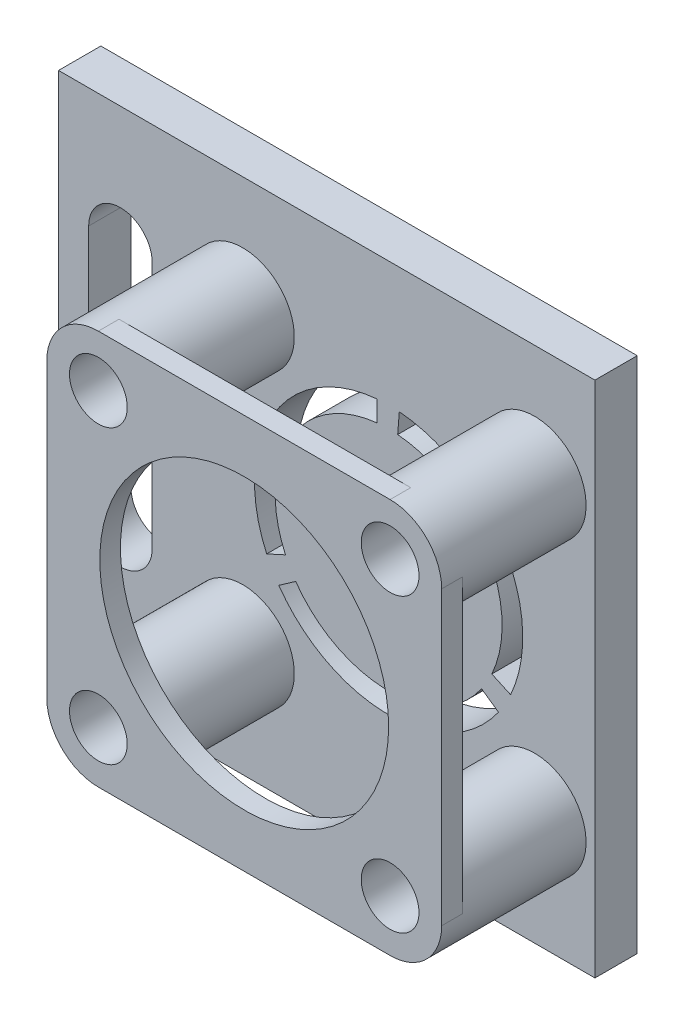
SolidWorks part; units mm, degrees
ref_plane "Front Plane" through (0, 0, 0) normal (0, 0, 1) x (1, 0, 0)
ref_plane "Top Plane" through (0, 0, 0) normal (0, 1, 0) x (1, 0, 0)
ref_plane "Right Plane" through (0, 0, 0) normal (1, 0, 0) x (0, 0, -1)
sketch "Sketch1" plane through (0, 0, 0) normal (0, 0, 1) x (1, 0, 0)
  line L1 (-13, -12.55) -> (13, -12.55)
  line L2 (-13, -12.55) -> (-13, 12.55)
  line L3 (-13, 12.55) -> (13, 12.55)
  line L4 (13, -12.55) -> (13, 12.55)
  line L5 (-13, -12.55) -> (13, 12.55) construction
  line L6 (-13, 12.55) -> (13, -12.55) construction
  point P0 (0, 0)
  dimension "D1" = 26
  dimension "D2" = 25.1
extrude "Boss-Extrude1" add sketch "Sketch1" along normal blind 2.05
sketch "Sketch2" plane through (0, 0, 2.05) normal (0, 0, 1) x (1, 0, 0)
  line L0 (-10, 6.75) -> (-10, -5.25) construction
  line L1 (-8.46, 6.75) -> (-8.46, -5.25)
  line L2 (-11.54, 6.75) -> (-11.54, -5.25)
  line L3 (13, 12.55) -> (-13, 12.55) construction
  line L4 (2.438, 5.4712) -> (2.438, 6.4757)
  line L5 (3.5177, 6.4794) -> (3.438, 5.4825)
  line L6 (8.9115, -2.7025) -> (8.0021, -2.2868)
  line L7 (7.5053, -3.1547) -> (8.3245, -3.7282)
  line L8 (-2.3245, -3.7282) -> (-1.5053, -3.1547)
  line L9 (-2.9115, -2.7025) -> (-2.0021, -2.2868)
  line L10 (13, -12.55) -> (13, 12.55) construction
  arc A0 (-8.46, 6.75) -> (-11.54, 6.75) centre (-10, 6.75) ccw
  arc A1 (-11.54, -5.25) -> (-8.46, -5.25) centre (-10, -5.25) ccw
  circle A3 centre (3, 0) radius 6.5
  circle A4 centre (3, 0) radius 5.5
  point P2 (-10, 0.75)
  dimension "D2" = 1.54
  dimension "D4" = 10
  dimension "D5" = 13
  dimension "D6" = 5.8
  dimension "D1" = 12
  dimension "D3" = 13
  dimension "D9" = 1
  dimension "D10" = 110
  dimension "D11" = 110
  dimension "D12" = 1
  dimension "D8" = 1
extrude "Cut-Extrude1" cut sketch "Sketch2" against normal through all
sketch "Sketch3" plane through (0, 0, 2.05) normal (0, 0, 1) x (1, 0, 0)
  line L0 (-4.0711, -7.0711) -> (10.0711, 7.0711) construction
  line L1 (-4.0711, 7.0711) -> (10.0711, -7.0711) construction
  circle A0 centre (-4.0711, 7.0711) radius 2.5
  circle A1 centre (10.0711, 7.0711) radius 2.5
  circle A2 centre (10.0711, -7.0711) radius 2.5
  circle A3 centre (-4.0711, -7.0711) radius 2.5
  arc A4 (-1.5053, -3.1547) -> (7.5053, -3.1547) centre (3, 0) ccw construction
  arc A5 (-1.5053, -3.1547) -> (7.5053, -3.1547) centre (3, 0) ccw
  dimension "D2" = 5
  dimension "D6" = 10
  dimension "D5" = 90
extrude "Boss-Extrude2" add sketch "Sketch3" along normal blind 6 contours A0 | A1 | A2 | A3
sketch "Sketch4" plane through (0, 0, 8.05) normal (0, 0, 1) x (1, 0, 0)
  line L4 (-4.0711, 9.5711) -> (10.0711, 9.5711)
  line L5 (12.5711, 7.0711) -> (12.5711, -7.0711)
  line L6 (-6.5711, -7.0711) -> (-6.5711, 7.0711)
  line L8 (10.0711, -9.5711) -> (-4.0711, -9.5711)
  circle A2 centre (-4.0711, -7.0711) radius 2.5 construction
  circle A3 centre (10.0711, -7.0711) radius 2.5 construction
  circle A4 centre (10.0711, 7.0711) radius 2.5 construction
  circle A5 centre (-4.0711, 7.0711) radius 2.5 construction
  arc A6 (-6.5711, -7.0711) -> (-4.0711, -9.5711) centre (-4.0711, -7.0711) ccw
  arc A7 (10.0711, -9.5711) -> (12.5711, -7.0711) centre (10.0711, -7.0711) ccw
  arc A8 (12.5711, 7.0711) -> (10.0711, 9.5711) centre (10.0711, 7.0711) ccw
  arc A9 (-4.0711, 9.5711) -> (-6.5711, 7.0711) centre (-4.0711, 7.0711) ccw
  circle A10 centre (3, 0) radius 7
  point P13 (3, 9.5711)
  point P22 (-6.5711, 0)
  dimension "D1" = 14
extrude "Boss-Extrude3" add sketch "Sketch4" along normal blind 1
sketch "Sketch5" plane through (0, 0, 9.05) normal (0, 0, 1) x (1, 0, 0)
  circle A0 centre (10.0711, 7.0711) radius 2.5 construction
  circle A1 centre (10.0711, -7.0711) radius 2.5 construction
  circle A2 centre (-4.0711, 7.0711) radius 2.5 construction
  circle A3 centre (-4.0711, -7.0711) radius 2.5 construction
  circle A4 centre (10.0711, 7.0711) radius 2.5
  circle A5 centre (10.0711, -7.0711) radius 2.5
  circle A6 centre (-4.0711, 7.0711) radius 2.5
  circle A7 centre (-4.0711, -7.0711) radius 2.5
  circle A8 centre (-4.0711, -7.0711) radius 1.4
  circle A9 centre (-4.0711, 7.0711) radius 1.4
  circle A10 centre (10.0711, 7.0711) radius 1.4
  circle A11 centre (10.0711, -7.0711) radius 1.4
  dimension "D1" = 2.8
extrude "Cut-Extrude2" cut sketch "Sketch5" against normal up to surface (9.05 mm away) contours A8 | A9 | A10 | A11 up to face at (-10, 0.75, 0)
ref_plane "Plane1" [suppressed] through (0, 0, 5) normal (0, 0, 1) x (1, 0, 0)
sketch "Sketch7" [suppressed] plane through (0, 0, 5) normal (0, 0, 1) x (1, 0, 0)
  line L0 (19.205, -8.5711) -> (18.7482, -8.5711)
  line L1 (20.9371, -8.5711) -> (21.8031, -7.0711)
  line L2 (21.8031, -7.0711) -> (20.9371, -5.5711)
  line L3 (20.9371, -5.5711) -> (19.205, -5.5711)
  line L4 (19.205, -5.5711) -> (18.339, -7.0711)
  line L5 (18.339, -7.0711) -> (19.205, -8.5711)
  line L6 (19.205, -8.5711) -> (20.9371, -8.5711)
  line L7 (20.9371, -5.5711) -> (20.7087, -5.1754)
  line L8 (20.9371, 5.5711) -> (20.7087, 5.1754)
  line L9 (21.8031, 7.0711) -> (20.9371, 8.5711)
  line L10 (20.9371, 8.5711) -> (19.205, 8.5711)
  line L11 (19.205, 8.5711) -> (18.339, 7.0711)
  line L12 (18.339, 7.0711) -> (19.205, 5.5711)
  line L13 (19.205, 5.5711) -> (20.9371, 5.5711)
  line L14 (20.9371, 5.5711) -> (21.8031, 7.0711)
  line L15 (19.205, 8.5711) -> (18.7482, 8.5711)
  line L17 (6.795, -5.5711) -> (5.0629, -5.5711)
  line L18 (5.0629, -5.5711) -> (4.1969, -7.0711)
  line L19 (4.1969, -7.0711) -> (5.0629, -8.5711)
  line L20 (5.0629, -8.5711) -> (6.795, -8.5711)
  line L21 (6.795, -8.5711) -> (7.661, -7.0711)
  line L22 (7.661, -7.0711) -> (6.795, -5.5711)
  line L23 (7.661, 7.0711) -> (6.795, 8.5711)
  line L24 (6.795, 8.5711) -> (5.0629, 8.5711)
  line L25 (5.0629, 8.5711) -> (4.1969, 7.0711)
  line L26 (4.1969, 7.0711) -> (5.0629, 5.5711)
  line L27 (5.0629, 5.5711) -> (6.795, 5.5711)
  line L28 (6.795, 5.5711) -> (7.661, 7.0711)
  line L29 (6.795, 8.5711) -> (7.2518, 8.5711)
  line L30 (5.0629, 5.5711) -> (5.2913, 5.1754)
  line L31 (6.795, -8.5711) -> (7.2518, -8.5711)
  line L32 (5.0629, -5.5711) -> (5.2913, -5.1754)
  circle A0 centre (20.0711, -7.0711) radius 2 construction
  circle A1 centre (20.0711, -7.0711) radius 2
  circle A2 centre (20.0711, -7.0711) radius 1.5 construction
  circle A3 centre (20.0711, 7.0711) radius 2 construction
  circle A4 centre (20.0711, 7.0711) radius 2
  circle A5 centre (20.0711, 7.0711) radius 1.5 construction
  circle A7 centre (5.9289, 7.0711) radius 2 construction
  circle A8 centre (5.9289, -7.0711) radius 2 construction
  circle A9 centre (5.9289, 7.0711) radius 2
  circle A10 centre (5.9289, -7.0711) radius 2
  circle A11 centre (5.9289, -7.0711) radius 1.5 construction
  circle A12 centre (5.9289, 7.0711) radius 1.5 construction
  dimension "D1" = 3
  dimension "D2" = 3
  dimension "D3" = 3
  dimension "D4" = 3
extrude "Cut-Extrude3" [suppressed] cut sketch "Sketch7" along normal blind 1
